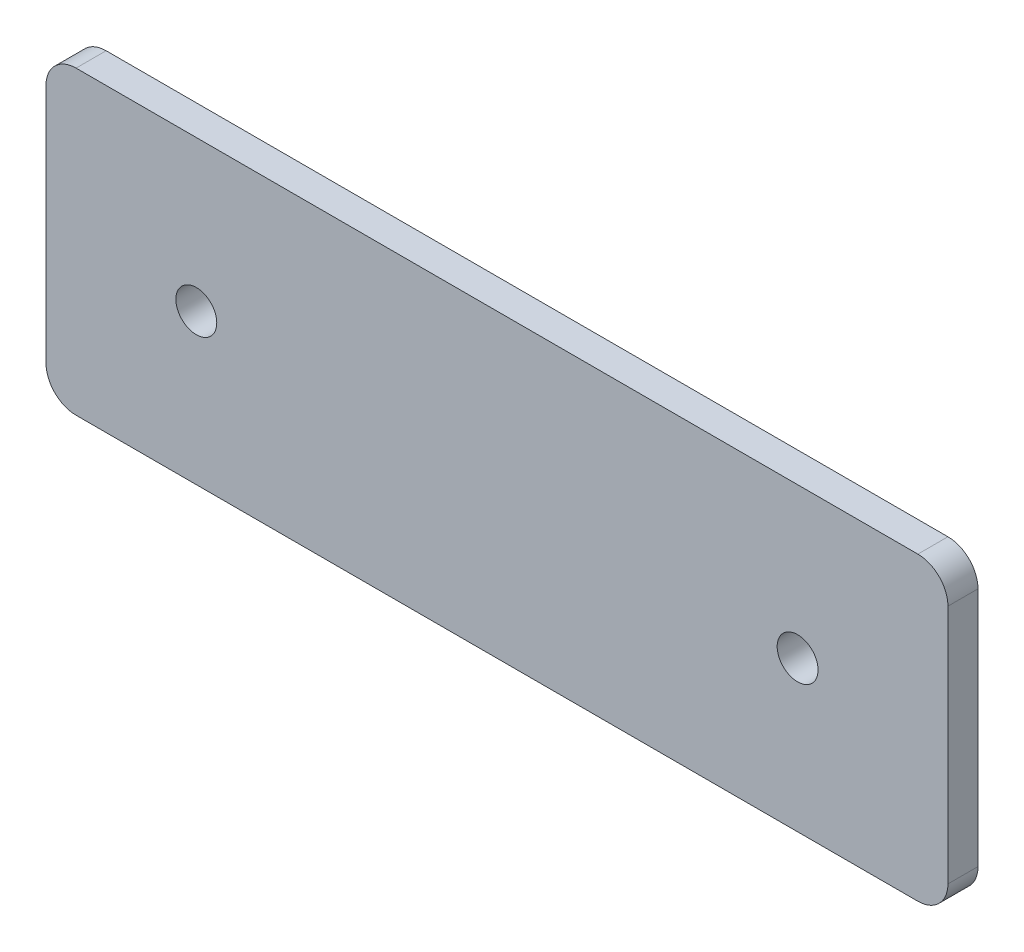
SolidWorks part; units mm, degrees
ref_plane "前视基准面" through (0, 0, 0) normal (0, 0, 1) x (1, 0, 0)
ref_plane "上视基准面" through (0, 0, 0) normal (0, 1, 0) x (1, 0, 0)
ref_plane "右视基准面" through (0, 0, 0) normal (1, 0, 0) x (0, 0, -1)
sketch "草图1" plane through (0, 0, 0) normal (0, 0, 1) x (1, 0, 0)
  line L1 (-70, 25) -> (70, 25)
  line L2 (-75, 20) -> (-75, -20)
  line L3 (-70, -25) -> (70, -25)
  line L4 (75, 20) -> (75, -20)
  line L5 (-75, 25) -> (75, -25) construction
  line L6 (-75, -25) -> (75, 25) construction
  arc A0 (70, -25) -> (75, -20) centre (70, -20) ccw
  arc A1 (75, 20) -> (70, 25) centre (70, 20) ccw
  arc A2 (-70, 25) -> (-75, 20) centre (-70, 20) ccw
  arc A3 (-70, -25) -> (-75, -20) centre (-70, -20) cw
  point P0 (0, 0)
  dimension "D3" = 5
  dimension "D4" = 5
  dimension "D1" = 150
  dimension "D2" = 50
extrude "凸台-拉伸1" add sketch "草图1" along normal blind 5
hole_wizard "M8 螺纹槽口的螺纹槽口钻头2" positions "草图2" profile "草图3" size "M8" standard "GB" slot yes end condition through all
sketch "草图2" plane through (0, 0, 5) normal (0, 0, 1) x (1, 0, 0)
  point P0 (-50, 0)
  point P2 (50, 0)
  dimension "D1" = 50
  dimension "D2" = 50
sketch "草图3" plane through (-50, 0, 5) normal (1, 0, 0) x (0, -1, 0)
  line L0 (0, 0) -> (0, 5)
  line L1 (0, 5) -> (3.4, 5)
  line L2 (3.4, 5) -> (3.4, 0)
  line L5 (3.4, 0) -> (0, 0)
  line L11 (0, -6.35) -> (0, 107.95) construction
  dimension "通孔孔直径" = 6.8
  dimension "通孔孔深度" = 5
